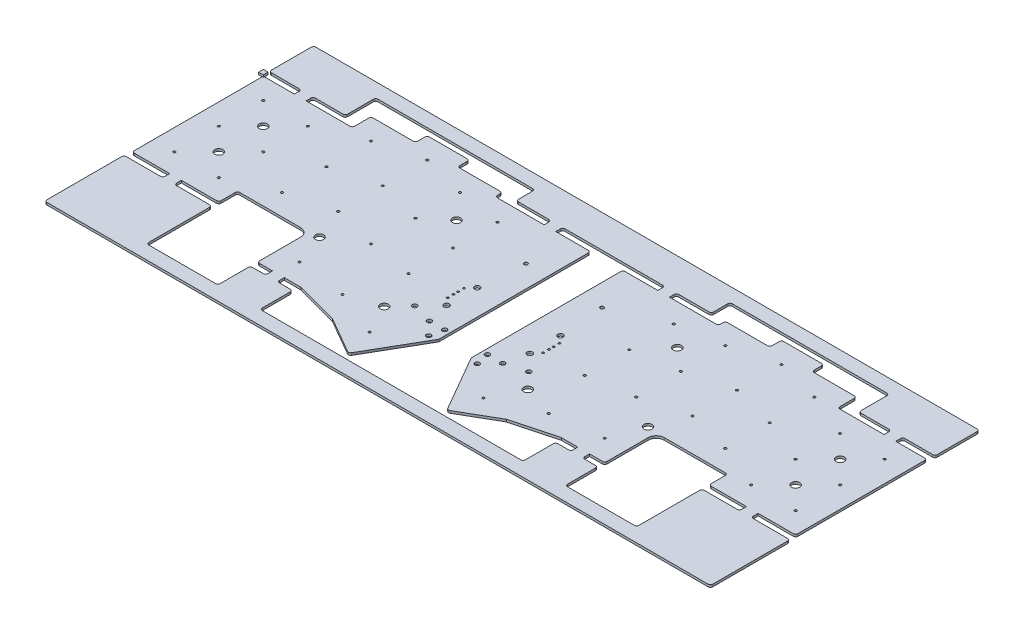
SolidWorks part; units mm, degrees
ref_plane "Front Plane" through (0, 0, 0) normal (0, 0, 1) x (1, 0, 0)
ref_plane "Top Plane" through (0, 0, 0) normal (0, 1, 0) x (1, 0, 0)
ref_plane "Right Plane" through (0, 0, 0) normal (1, 0, 0) x (0, 0, -1)
sketch "Sketch1" plane through (0, 0, 0) normal (0, 1, 0) x (1, 0, 0)
  line L0 (117.3, 5) -> (135.08, 5) construction
  line L1 (0, 0) -> (0, -68.58) construction
  line L2 (0, -19.05) -> (19.05, -19.05) construction
  line L3 (0, 0) -> (19.05, 0) construction
  line L4 (0, 0) -> (0, -19.05) construction
  line L5 (0, -19.05) -> (19.05, -19.05) construction
  line L6 (19.05, 0) -> (19.05, -19.05) construction
  line L7 (0, 0) -> (19.05, -19.05) construction
  line L8 (0, -19.05) -> (19.05, 0) construction
  line L9 (0, -19.05) -> (0, -38.1) construction
  line L10 (0, -38.1) -> (19.05, -38.1) construction
  line L11 (19.05, -19.05) -> (19.05, -38.1) construction
  line L12 (0, -19.05) -> (19.05, -38.1) construction
  line L13 (0, -38.1) -> (19.05, -19.05) construction
  line L14 (0, -38.1) -> (19.05, -38.1) construction
  line L15 (0, -38.1) -> (0, -57.15) construction
  line L16 (0, -57.15) -> (19.05, -57.15) construction
  line L17 (19.05, -38.1) -> (19.05, -57.15) construction
  line L18 (0, -38.1) -> (19.05, -57.15) construction
  line L19 (0, -57.15) -> (19.05, -38.1) construction
  line L20 (19.05, -19.05) -> (38.1, -19.05) construction
  line L21 (19.05, 0) -> (38.1, 0) construction
  line L22 (19.05, 0) -> (19.05, -19.05) construction
  line L23 (19.05, -19.05) -> (38.1, -19.05) construction
  line L24 (38.1, -11.05) -> (38.1, 0) construction
  line L25 (19.05, 0) -> (38.1, -19.05) construction
  line L26 (19.05, -19.05) -> (38.1, 0) construction
  line L27 (19.05, -19.05) -> (19.05, -38.1) construction
  line L28 (19.05, -38.1) -> (38.1, -38.1) construction
  line L29 (38.1, -19.05) -> (38.1, -38.1) construction
  line L30 (19.05, -19.05) -> (38.1, -38.1) construction
  line L31 (19.05, -38.1) -> (38.1, -19.05) construction
  line L32 (19.05, -38.1) -> (38.1, -38.1) construction
  line L33 (19.05, -38.1) -> (19.05, -57.15) construction
  line L34 (19.05, -57.15) -> (38.1, -57.15) construction
  line L35 (38.1, -38.1) -> (38.1, -49.15) construction
  line L36 (19.05, -38.1) -> (38.1, -57.15) construction
  line L37 (19.05, -57.15) -> (38.1, -38.1) construction
  line L38 (38.1, -11.05) -> (57.15, -11.05) construction
  line L39 (38.1, 8) -> (57.15, 8) construction
  line L40 (38.1, 0) -> (38.1, 8) construction
  line L41 (38.1, -11.05) -> (57.15, -11.05) construction
  line L42 (57.15, 8) -> (57.15, -11.05) construction
  line L43 (38.1, 8) -> (57.15, -11.05) construction
  line L44 (38.1, -11.05) -> (57.15, 8) construction
  line L45 (38.1, -11.05) -> (38.1, -30.1) construction
  line L46 (38.1, -30.1) -> (57.15, -30.1) construction
  line L47 (57.15, -11.05) -> (57.15, -30.1) construction
  line L48 (38.1, -11.05) -> (57.15, -30.1) construction
  line L49 (38.1, -30.1) -> (57.15, -11.05) construction
  line L50 (38.1, -30.1) -> (57.15, -30.1) construction
  line L51 (38.1, -49.15) -> (38.1, -57.15) construction
  line L52 (38.1, -49.15) -> (57.15, -49.15) construction
  line L53 (76.2, 8) -> (76.2, 13) construction
  line L54 (38.1, -30.1) -> (57.15, -49.15) construction
  line L55 (38.1, -49.15) -> (57.15, -30.1) construction
  line L56 (57.15, -6.05) -> (76.2, -6.05) construction
  line L57 (57.15, 13) -> (76.2, 13) construction
  line L58 (57.15, 8) -> (57.15, 13) construction
  line L59 (57.15, -6.05) -> (76.2, -6.05) construction
  line L60 (95.25, 5) -> (95.25, 8) construction
  line L61 (57.15, 13) -> (76.2, -6.05) construction
  line L62 (57.15, -6.05) -> (76.2, 13) construction
  line L63 (57.15, -6.05) -> (57.15, -25.1) construction
  line L64 (57.15, -25.1) -> (76.2, -25.1) construction
  line L65 (76.2, -6.05) -> (76.2, -25.1) construction
  line L66 (57.15, -6.05) -> (76.2, -25.1) construction
  line L67 (57.15, -25.1) -> (76.2, -6.05) construction
  line L68 (57.15, -25.1) -> (76.2, -25.1) construction
  line L69 (57.15, -25.1) -> (57.15, -44.15) construction
  line L70 (57.15, -44.15) -> (76.2, -44.15) construction
  line L71 (76.2, -25.1) -> (76.2, -44.15) construction
  line L72 (57.15, -25.1) -> (76.2, -44.15) construction
  line L73 (57.15, -44.15) -> (76.2, -25.1) construction
  line L74 (76.2, -11.05) -> (95.25, -11.05) construction
  line L75 (76.2, 8) -> (95.25, 8) construction
  line L76 (76.2, 8) -> (76.2, -11.05) construction
  line L77 (76.2, -11.05) -> (95.25, -11.05) construction
  line L78 (57.15, -49.15) -> (57.15, -44.15) construction
  line L79 (76.2, 8) -> (95.25, -11.05) construction
  line L80 (76.2, -11.05) -> (95.25, 8) construction
  line L81 (76.2, -11.05) -> (76.2, -30.1) construction
  line L82 (76.2, -30.1) -> (95.25, -30.1) construction
  line L83 (95.25, -11.05) -> (95.25, -30.1) construction
  line L84 (76.2, -11.05) -> (95.25, -30.1) construction
  line L85 (76.2, -30.1) -> (95.25, -11.05) construction
  line L86 (76.2, -30.1) -> (95.25, -30.1) construction
  line L87 (76.2, -30.1) -> (76.2, -49.15) construction
  line L88 (76.2, -49.15) -> (95.25, -49.15) construction
  line L89 (95.25, -30.1) -> (95.25, -49.15) construction
  line L90 (76.2, -30.1) -> (95.25, -49.15) construction
  line L91 (76.2, -49.15) -> (95.25, -30.1) construction
  line L92 (95.25, -14.05) -> (114.3, -14.05) construction
  line L93 (95.25, 5) -> (114.3, 5) construction
  line L94 (95.25, 5) -> (95.25, -14.05) construction
  line L95 (95.25, -14.05) -> (114.3, -14.05) construction
  line L96 (114.3, 5) -> (114.3, -14.05) construction
  line L97 (95.25, 5) -> (114.3, -14.05) construction
  line L98 (95.25, -14.05) -> (114.3, 5) construction
  line L99 (95.25, -14.05) -> (95.25, -33.1) construction
  line L100 (95.25, -33.1) -> (114.3, -33.1) construction
  line L101 (114.3, -14.05) -> (114.3, -33.1) construction
  line L102 (95.25, -14.05) -> (114.3, -33.1) construction
  line L103 (95.25, -33.1) -> (114.3, -14.05) construction
  line L104 (95.25, -33.1) -> (114.3, -33.1) construction
  line L105 (95.25, -33.1) -> (95.25, -52.15) construction
  line L106 (95.25, -52.15) -> (114.3, -52.15) construction
  line L107 (114.3, -33.1) -> (114.3, -52.15) construction
  line L108 (95.25, -33.1) -> (114.3, -52.15) construction
  line L109 (95.25, -52.15) -> (114.3, -33.1) construction
  line L110 (67.65, -52.15) -> (86.7, -52.15) construction
  line L117 (67.65, -52.15) -> (86.7, -52.15) construction
  line L118 (67.65, -52.15) -> (67.65, -71.2) construction
  line L119 (67.65, -71.2) -> (86.7, -71.2) construction
  line L120 (86.7, -52.15) -> (86.7, -71.2) construction
  line L121 (67.65, -52.15) -> (86.7, -71.2) construction
  line L122 (67.65, -71.2) -> (86.7, -52.15) construction
  line L124 (91.6305, -52.7991) -> (110.0314, -57.7296) construction
  line L125 (91.6305, -52.7991) -> (86.7, -71.2) construction
  line L126 (86.7, -71.2) -> (105.1009, -76.1305) construction
  line L127 (110.0314, -57.7296) -> (105.1009, -76.1305) construction
  line L128 (91.6305, -52.7991) -> (105.1009, -76.1305) construction
  line L129 (86.7, -71.2) -> (110.0314, -57.7296) construction
  line L130 (114.6259, -59.6327) -> (131.1237, -69.1577) construction
  line L131 (114.6259, -59.6327) -> (105.1009, -76.1305) construction
  line L132 (105.1009, -76.1305) -> (121.5987, -85.6555) construction
  line L133 (131.1237, -69.1577) -> (121.5987, -85.6555) construction
  line L134 (114.6259, -59.6327) -> (121.5987, -85.6555) construction
  line L135 (105.1009, -76.1305) -> (131.1237, -69.1577) construction
  line L152 (135.08, -28.02) -> (135.08, 5) construction
  line L153 (126.19, -12.51) -> (126.19, -29.02) construction
  line L154 (114.3, 5) -> (117.3, 5) construction
  line L155 (135.58, 3.5) -> (135.58, -60.1712)
  line L156 (124.68, -33.1) -> (124.68, -46.25) construction
  line L157 (135.08, -33.1) -> (121.08, -33.1) construction
  line L158 (95.75, 4.5) -> (114.3, 4.5)
  line L159 (94.75, 5.5) -> (94.75, 6.5)
  line L160 (76.7, 7.5) -> (93.75, 7.5)
  line L161 (75.7, 8.5) -> (75.7, 11.5)
  line L162 (58.65, 12.5) -> (74.7, 12.5)
  line L163 (57.65, 8.5) -> (57.65, 11.5)
  line L164 (39.6, 7.5) -> (56.65, 7.5)
  line L165 (38.6, 0.5) -> (38.6, 6.5)
  line L166 (19.05, -0.5) -> (37.6, -0.5)
  line L167 (1.5, -0.5) -> (19.05, -0.5)
  line L168 (0.5, -1.5) -> (0.5, -19.05)
  line L169 (0.5, -19.05) -> (0.5, -38.1)
  line L170 (0.5, -38.1) -> (0.5, -55.65)
  line L171 (1.5, -56.65) -> (19.05, -56.65)
  line L172 (19.05, -56.65) -> (36.6, -56.65)
  line L173 (37.6, -49.65) -> (37.6, -55.65)
  line L174 (38.6, -48.65) -> (57.15, -48.65)
  line L175 (114.3, 4.5) -> (134.58, 4.5)
  line L176 (68.15, -52.15) -> (68.15, -69.7)
  line L177 (69.15, -70.7) -> (86.7658, -70.7)
  line L178 (86.7658, -70.7) -> (105.2939, -75.6646)
  line L179 (105.2939, -75.6646) -> (120.5496, -84.4725)
  line L180 (130.6907, -68.9077) -> (121.9157, -84.1065)
  line L181 (130.6907, -68.9077) -> (135.446, -60.6712)
  line L182 (57.15, -48.65) -> (64.65, -48.65)
  line L183 (0.5, -38.1) -> (0.5, -56.65) construction
  line L184 (0.5, -56.65) -> (19.05, -56.65) construction
  line L185 (19.05, -56.65) -> (37.6, -56.65) construction
  line L186 (37.6, -48.65) -> (37.6, -56.65) construction
  line L187 (37.6, -48.65) -> (57.15, -48.65) construction
  line L188 (68.15, -52.15) -> (68.15, -70.7) construction
  line L189 (68.15, -70.7) -> (86.7658, -70.7) construction
  line L190 (105.2939, -75.6646) -> (121.4157, -84.9725) construction
  line L191 (130.6907, -68.9077) -> (121.4157, -84.9725) construction
  line L192 (94.75, 4.5) -> (114.3, 4.5) construction
  line L193 (94.75, 4.5) -> (94.75, 7.5) construction
  line L194 (75.7, 7.5) -> (94.75, 7.5) construction
  line L195 (75.7, 7.5) -> (75.7, 12.5) construction
  line L196 (57.65, 12.5) -> (75.7, 12.5) construction
  line L197 (57.65, 7.5) -> (57.65, 12.5) construction
  line L198 (38.6, 7.5) -> (57.65, 7.5) construction
  line L199 (38.6, -0.5) -> (38.6, 7.5) construction
  line L200 (19.05, -0.5) -> (38.6, -0.5) construction
  line L201 (0.5, -0.5) -> (19.05, -0.5) construction
  line L202 (0.5, -0.5) -> (0.5, -19.05) construction
  line L203 (72.2, -48.15) -> (72.2, -44.15) construction
  line L204 (72.2, -48.15) -> (76.2, -48.15) construction
  line L205 (72.2, -48.15) -> (72.2, -52.15) construction
  line L206 (95.25, -11.05) -> (95.25, -14.05) construction
  line L207 (110.0314, -57.7296) -> (112.4539, -58.3787) construction
  line L208 (112.4539, -58.3787) -> (114.6259, -59.6327) construction
  line L209 (135.08, -33.1) -> (135.08, -46.25) construction
  line L210 (135.08, 4) -> (117.3, 4) construction
  line L211 (135.08, 4) -> (135.08, -29.02) construction
  line L212 (135.08, -29.02) -> (117.3, -29.02) construction
  line L213 (117.3, 4) -> (117.3, -29.02) construction
  line L214 (135.08, 4) -> (117.3, -29.02) construction
  line L215 (135.08, -29.02) -> (117.3, 4) construction
  line L216 (135.08, -46.25) -> (121.08, -46.25) construction
  line L217 (121.08, -33.1) -> (121.08, -46.25) construction
  line L218 (135.08, -33.1) -> (121.08, -46.25) construction
  line L219 (135.08, -46.25) -> (121.08, -33.1) construction
  line L220 (121.08, -39.675) -> (135.08, -39.675) construction
  line L221 (122.08, -32.9301) -> (122.08, -48.5098) construction
  line L222 (133.33, -49.25) -> (133.33, -55.75) construction
  line L223 (135.08, -49.25) -> (131.58, -49.25) construction
  line L224 (135.08, -49.25) -> (135.08, -55.75) construction
  line L225 (135.08, -55.75) -> (131.58, -55.75) construction
  line L226 (131.58, -49.25) -> (131.58, -55.75) construction
  line L227 (135.08, -49.25) -> (131.58, -55.75) construction
  line L228 (135.08, -55.75) -> (131.58, -49.25) construction
  line L229 (133.33, -55.75) -> (126.83, -55.75) construction
  line L230 (118.08, -53.25) -> (132.08, -61.3329) construction
  line L231 (118.08, -53.25) -> (132.08, -53.25) construction
  line L232 (132.08, -61.3329) -> (132.08, -53.25) construction
  arc A0 (64.65, -48.65) -> (68.15, -52.15) centre (64.65, -52.15) cw
  arc A1 (0.5, -55.65) -> (1.5, -56.65) centre (1.5, -55.65) ccw
  arc A2 (36.6, -56.65) -> (37.6, -55.65) centre (36.6, -55.65) ccw
  arc A3 (37.6, -49.65) -> (38.6, -48.65) centre (38.6, -49.65) cw
  arc A4 (68.15, -69.7) -> (69.15, -70.7) centre (69.15, -69.7) ccw
  arc A5 (120.5496, -84.4725) -> (121.9157, -84.1065) centre (121.0496, -83.6065) ccw
  arc A6 (135.446, -60.6712) -> (135.58, -60.1712) centre (134.58, -60.1712) ccw
  arc A7 (134.58, 4.5) -> (135.58, 3.5) centre (134.58, 3.5) cw
  arc A8 (95.75, 4.5) -> (94.75, 5.5) centre (95.75, 5.5) cw
  arc A9 (94.75, 6.5) -> (93.75, 7.5) centre (93.75, 6.5) ccw
  arc A10 (76.7, 7.5) -> (75.7, 8.5) centre (76.7, 8.5) cw
  arc A11 (75.7, 11.5) -> (74.7, 12.5) centre (74.7, 11.5) ccw
  arc A12 (58.65, 12.5) -> (57.65, 11.5) centre (58.65, 11.5) ccw
  arc A13 (57.65, 8.5) -> (56.65, 7.5) centre (56.65, 8.5) cw
  arc A14 (39.6, 7.5) -> (38.6, 6.5) centre (39.6, 6.5) ccw
  arc A15 (38.6, 0.5) -> (37.6, -0.5) centre (37.6, 0.5) cw
  arc A16 (1.5, -0.5) -> (0.5, -1.5) centre (1.5, -1.5) ccw
  circle A17 centre (19.05, -19.05) radius 1.75
  circle A18 centre (19.05, -38.1) radius 1.75
  circle A19 centre (72.2, -48.15) radius 1.75
  circle A20 centre (111.7784, -60.0095) radius 1.75
  circle A21 centre (95.25, -12.55) radius 1.75
  circle A22 centre (9.525, -9.525) radius 0.5
  circle A23 centre (28.575, -9.525) radius 0.5
  circle A24 centre (9.525, -28.575) radius 0.5
  circle A25 centre (28.575, -28.575) radius 0.5
  circle A26 centre (9.525, -47.625) radius 0.5
  circle A27 centre (28.575, -47.625) radius 0.5
  circle A28 centre (47.625, -39.625) radius 0.5
  circle A29 centre (47.625, -20.575) radius 0.5
  circle A30 centre (47.625, -1.525) radius 0.5
  circle A31 centre (66.675, 3.475) radius 0.5
  circle A32 centre (66.675, -15.575) radius 0.5
  circle A33 centre (66.675, -34.625) radius 0.5
  circle A34 centre (85.725, -39.625) radius 0.5
  circle A35 centre (85.725, -20.575) radius 0.5
  circle A36 centre (85.725, -1.525) radius 0.5
  circle A37 centre (104.775, -4.525) radius 0.5
  circle A38 centre (104.775, -23.575) radius 0.5
  circle A39 centre (104.775, -42.625) radius 0.5
  circle A40 centre (77.175, -61.675) radius 0.5
  circle A41 centre (98.3657, -64.4648) radius 0.5
  circle A42 centre (118.1123, -72.6441) radius 0.5
  circle A45 centre (126.19, -13.78) radius 0.75
  circle A47 centre (124.68, -33.105) radius 1.15
  circle A48 centre (124.68, -46.245) radius 1.15
  circle A49 centre (122.08, -38.675) radius 0.45
  circle A50 centre (122.08, -36.175) radius 0.45
  circle A51 centre (122.08, -43.175) radius 0.45
  circle A52 centre (122.08, -40.675) radius 0.45
  circle A54 centre (133.33, -55.75) radius 1
  circle A55 centre (126.83, -55.75) radius 1
  circle A56 centre (118.08, -53.25) radius 1
  circle A57 centre (132.08, -61.3329) radius 1
  circle A58 centre (118.08, -53.25) radius 2.5 construction
  circle A59 centre (132.08, -61.3329) radius 2.5 construction
  point P3 (9.525, -9.525)
  point P9 (77.175, -61.675)
  point P10 (9.525, -28.575)
  point P16 (9.525, -47.625)
  point P21 (28.575, -9.525)
  point P25 (28.575, -28.575)
  point P27 (28.575, -47.625)
  point P32 (47.625, -1.525)
  point P36 (47.625, -20.575)
  point P38 (47.625, -39.625)
  point P44 (66.675, 3.475)
  point P48 (66.675, -15.575)
  point P50 (66.675, -34.625)
  point P56 (85.725, -1.525)
  point P60 (85.725, -20.575)
  point P62 (85.725, -39.625)
  point P66 (98.3657, -64.4648)
  point P68 (104.775, -4.525)
  point P72 (104.775, -23.575)
  point P74 (104.775, -42.625)
  point P92 (118.1123, -72.6441)
  point P131 (135.58, 4.5)
  point P215 (128.08, -39.675)
  point P243 (133.33, -52.5)
  dimension "D13" = 0.5
  dimension "D14" = 1
  dimension "D16" = 3.5
  dimension "D17" = 1
  dimension "D18" = 0.5
  dimension "D21" = 15.24
  dimension "D22" = 1.5
  dimension "D25" = 2.3
  dimension "D29" = 0.9
  dimension "D32" = 6.5
  dimension "D36" = 2
  dimension "D37" = 2
  dimension "D40" = 5
  dimension "D1" = 19.05
  dimension "D2" = 8
  dimension "D3" = 5
  dimension "D4" = 3
  dimension "D5" = 0.5
  dimension "D6" = 33.02
  dimension "D7" = 17.78
  dimension "D8" = 0.5
  dimension "D9" = 8.55
  dimension "D10" = 3
  dimension "D11" = 15
  dimension "D12" = 15
  dimension "D15" = 3
  dimension "D19" = 17.78
  dimension "D20" = 33.02
  dimension "D23" = 14
  dimension "D24" = 13.15
  dimension "D26" = 13.14
  dimension "D27" = 2
  dimension "D28" = 2.5
  dimension "D30" = 2.6
  dimension "D31" = 1
  dimension "D33" = 6.5
  dimension "D34" = 3.5
  dimension "D35" = 3
  dimension "D38" = 30
  dimension "D39" = 14
  dimension "D41" = 3.5
  dimension "D42" = 7
extrude "Boss-Extrude1" add sketch "Sketch1" along normal blind 1
sketch "Sketch2" plane through (0, 1, 0) normal (0, 1, 0) x (1, 0, 0)
  line L0 (0, 0) -> (0, -112.7699) construction
  line L1 (0, 0) -> (0, 28.891) construction
  line L2 (0, 15.5) -> (142.5, 15.5) construction
  line L3 (142.5, 15.5) -> (142.5, 21.5)
  line L4 (142.5, 21.5) -> (0, 21.5)
  line L5 (0, 21.5) -> (0, 15.5)
  line L6 (0, -59.65) -> (37.6, -59.65) construction
  line L7 (37.6, -59.65) -> (37.6, -87.6065)
  line L8 (37.6, -87.6065) -> (142.5, -87.6065) construction
  line L9 (142.5, -87.6065) -> (142.5, -93.6065)
  line L10 (142.5, -93.6065) -> (0, -93.6065)
  line L11 (0, -93.6065) -> (0, -59.65)
  line L12 (1.5, -56.65) -> (36.6, -56.65) construction
  line L13 (37.6, -55.65) -> (37.6, -49.65) construction
  line L14 (74.7, 12.5) -> (58.65, 12.5) construction
  line L15 (0, 15.5) -> (0, 2.5)
  line L17 (0, 2.5) -> (32.6, 2.5) construction
  line L19 (19.05, -56.65) -> (19.05, -59.65) construction
  line L20 (99.7656, -84.6065) -> (135.0004, -84.6065) construction
  line L21 (16.55, -59.65) -> (16.55, -53.65)
  line L22 (16.55, -53.65) -> (21.55, -53.65)
  line L23 (21.55, -53.65) -> (21.55, -59.65)
  line L24 (21.55, -59.65) -> (37.6, -59.65)
  line L25 (0, -59.65) -> (16.55, -59.65)
  line L35 (142.5, 15.5) -> (142.5, -87.6065) construction
  line L36 (37.6, -87.6065) -> (68.15, -87.6065)
  line L37 (0, 0) -> (-2, 0)
  line L38 (0, 0) -> (0, 2)
  line L39 (0, 2) -> (-2, 2)
  line L40 (-2, 0) -> (-2, 2)
  line L42 (77.175, -61.675) -> (77.175, -87.6065) construction
  line L47 (32.6, 2.5) -> (32.6, 15.5)
  line L48 (32.6, 15.5) -> (100.75, 15.5)
  line L49 (100.75, 15.5) -> (100.75, 7.5)
  line L50 (100.75, 7.5) -> (142.5, 7.5) construction
  line L52 (142.5, 7.5) -> (142.5, 15.5)
  line L53 (37.6, -0.5) -> (1.5, -0.5) construction
  line L54 (134.58, 4.5) -> (95.75, 4.5) construction
  line L55 (38.6, 6.5) -> (38.6, 0.5) construction
  line L56 (94.75, 5.5) -> (94.75, 6.5) construction
  line L57 (16.3, 2.5) -> (16.3, -1.0612) construction
  line L58 (100.75, 7.5) -> (100.75, 4.5) construction
  line L59 (135.58, 3.5) -> (135.58, 7.5) construction
  line L60 (100.75, 6) -> (135.58, 6) construction
  line L61 (118.165, 6) -> (118.165, 1.5) construction
  line L62 (100.75, 7.5) -> (115.665, 7.5)
  line L63 (115.665, 7.5) -> (115.665, 1.5)
  line L64 (115.665, 1.5) -> (120.665, 1.5)
  line L65 (120.665, 1.5) -> (120.665, 7.5)
  line L66 (120.665, 7.5) -> (142.5, 7.5)
  line L67 (0, 2.5) -> (13.8, 2.5)
  line L68 (13.8, 2.5) -> (13.8, -3.5)
  line L69 (13.8, -3.5) -> (18.8, -3.5)
  line L70 (18.8, -3.5) -> (18.8, 2.5)
  line L71 (18.8, 2.5) -> (32.6, 2.5)
  line L72 (68.15, -87.6065) -> (68.15, -73.7)
  line L73 (68.15, -73.7) -> (74.675, -73.7)
  line L74 (74.675, -73.7) -> (74.675, -67.7)
  line L75 (74.675, -67.7) -> (79.675, -67.7)
  line L76 (79.675, -67.7) -> (79.675, -73.7)
  line L77 (79.675, -73.7) -> (86.2, -73.7)
  line L79 (131.1204, -87.6065) -> (142.5, -87.6065)
  line L82 (86.2, -87.6065) -> (131.1204, -87.6065)
  line L85 (69.15, -70.7) -> (86.7658, -70.7) construction
  line L86 (68.15, -52.15) -> (68.15, -69.7) construction
  line L87 (86.2, -73.7) -> (86.2, -87.6065)
  arc A0 (120.5496, -84.4725) -> (121.9157, -84.1065) centre (121.0496, -83.6065) ccw construction
  point P53 (0, 0)
  dimension "D1" = 3
  dimension "D2" = 6
  dimension "D3" = 3
  dimension "D4" = 3
  dimension "D5" = 3
  dimension "D6" = 142.5
  dimension "D7" = 2
  dimension "D8" = 3
  dimension "D9" = 5
  dimension "D10" = 3
  dimension "D11" = 6
  dimension "D12" = 6
  dimension "D13" = 6
  dimension "D14" = 6
  dimension "D15" = 6
extrude "Boss-Extrude2" add sketch "Sketch2" along normal blind 1 from surface at -1 starting at face at (118.08, 0, 54.25)
fillet "Fillet1" radius 1 22 edges at (0, 0.5, 93.6065) (37.6, 0.5, 59.65) (21.55, 0.5, 59.65) (16.55, 0.5, 59.65) (0, 0.5, 59.65) (0, 0.5, -21.5) (37.6, 0.5, 87.6065) (32.6, 0.5, -15.5) (100.75, 0.5, -15.5) (120.665, 0.5, -7.5) (115.665, 0.5, -7.5) (100.75, 0.5, -7.5) (32.6, 0.5, -2.5) (18.8, 0.5, -2.5) (13.8, 0.5, -2.5) (0, 0.5, -2.5) (79.675, 0.5, 73.7) (74.675, 0.5, 73.7) (68.15, 0.5, 73.7) (68.15, 0.5, 87.6065) (86.2, 0.5, 73.7) (86.2, 0.5, 87.6065)
mirror "Mirror1" about plane through (142.5, 1, -3.5) normal (1, 0, 0) of bodies 103
